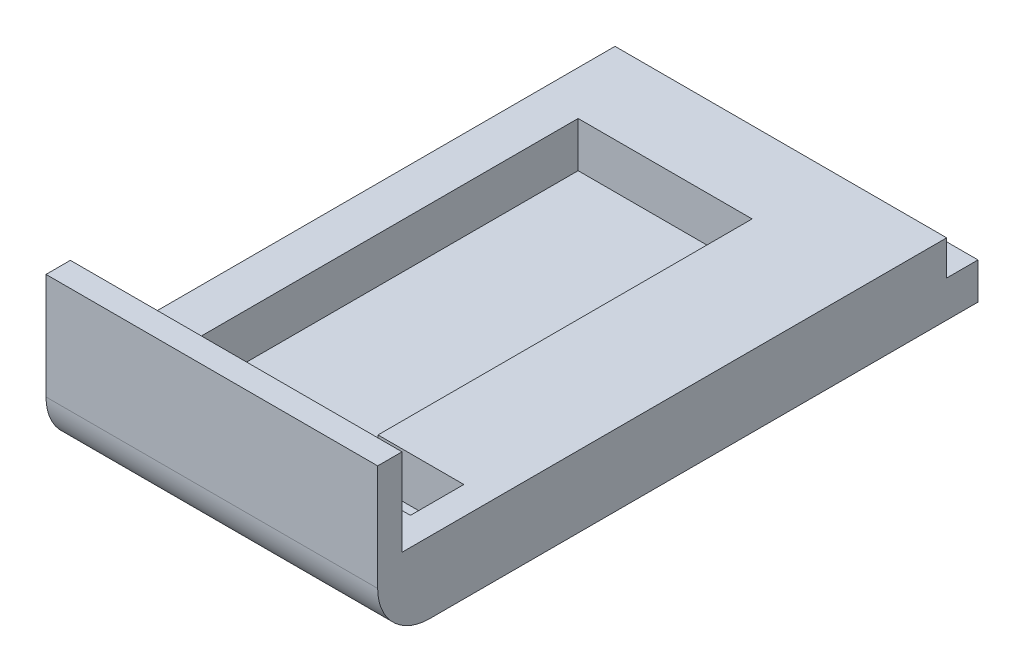
SolidWorks part; units mm, degrees
ref_plane "前视基准面" through (0, 0, 0) normal (0, 0, 1) x (1, 0, 0)
ref_plane "上视基准面" through (0, 0, 0) normal (0, 1, 0) x (1, 0, 0)
ref_plane "右视基准面" through (0, 0, 0) normal (1, 0, 0) x (0, 0, -1)
other "Configuration Table"
sketch "草图1" plane through (0, 0, 0) normal (1, 0, 0) x (0, 0, -1)
  line L0 (0, 0) -> (0, -1.1)
  line L1 (3, -4.1) -> (34.5, -4.1)
  line L2 (34.5, -4.1) -> (34.5, 0)
  line L3 (34.5, 0) -> (0, 0)
  arc A0 (3, -4.1) -> (0, -1.1) centre (3, -1.1) cw
  dimension "D3" = 3
  dimension "D1" = 34.5
  dimension "D2" = 4.1
extrude "凸台-拉伸1" add sketch "草图1" along normal blind 19.06
sketch "草图2" plane through (0, 0, 0) normal (0, 1, 0) x (1, 0, 0)
  line L0 (0, 34.5) -> (0, 0) construction
  line L1 (2.53, 28.05) -> (12.53, 28.05)
  line L2 (2.53, 28.05) -> (2.53, 4.05)
  line L3 (2.53, 4.05) -> (11.9779, 4.05)
  line L4 (12.53, 28.05) -> (12.53, 6.55)
  line L5 (19.06, 0) -> (0, 0) construction
  line L6 (12.53, 6.55) -> (17.4642, 6.55)
  line L7 (17.4642, 6.55) -> (17.4642, 4.05)
  line L10 (12.53, 3.479) -> (17.4642, 3.479)
  line L11 (17.4642, 3.479) -> (17.4642, 4.05)
  line L12 (12.53, 3.479) -> (11.9779, 3.479)
  line L13 (11.9779, 3.479) -> (11.9779, 4.05)
  dimension "D2" = 2.53
  dimension "D3" = 4.05
  dimension "D5" = 2.5
extrude "切除-拉伸1" cut sketch "草图2" against normal blind 2.6
sketch "草图3" plane through (0, 0, 0) normal (0, 1, 0) x (1, 0, 0)
  line L0 (19.06, 34.5) -> (19.06, 0) construction
  line L1 (19.06, 1.9) -> (0, 1.9)
  line L2 (19.06, 1.9) -> (19.06, 0)
  line L3 (19.06, 0) -> (0, 0)
  line L4 (0, 1.9) -> (0, 0)
  line L5 (0, 34.5) -> (0, 0) construction
  line L6 (19.06, 0) -> (0, 0) construction
extrude "凸台-拉伸2" add sketch "草图3" along normal blind 5
sketch "草图4" plane through (0, 0, 0) normal (-1, 0, 0) x (0, 0, 1)
  line L0 (-34.5, 0) -> (-1.9, 0) construction
  line L1 (-34.5, 0) -> (-32.7, 0)
  line L2 (-34.5, 0) -> (-34.5, -2)
  line L3 (-34.5, -2) -> (-32.7, -2)
  line L4 (-32.7, 0) -> (-32.7, -2)
  line L5 (-34.5, -4.1) -> (-34.5, 0) construction
  dimension "D1" = 1.8
  dimension "D2" = 2
extrude "切除-拉伸2" cut sketch "草图4" against normal up to next
sketch "草图5" plane through (19.06, 0, 0) normal (1, 0, 0) x (0, 0, -1)
  line L0 (32.7, 0) -> (1.9, 0) construction
  line L1 (1.9, 0) -> (1.4, 0)
  line L2 (1.9, 0) -> (1.9, 5)
  line L3 (1.9, 5) -> (1.4, 5)
  line L4 (1.4, 0) -> (1.4, 5)
  line L5 (1.9, 5) -> (1.9, 0) construction
  line L6 (0, 5) -> (1.9, 5) construction
  dimension "D1" = 0.5
extrude "切除-拉伸3" cut sketch "草图5" against normal through all
